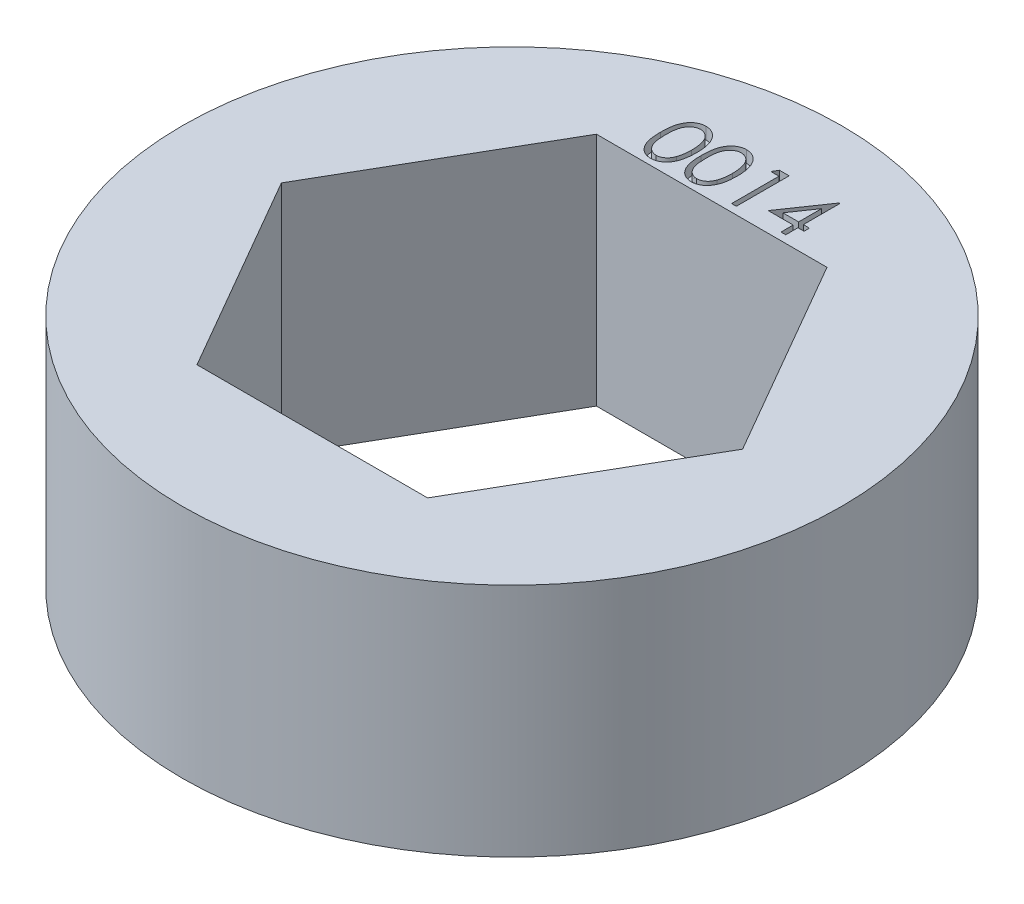
SolidWorks part; units mm, degrees
material "Nylon 101"
ref_plane "Front Plane" through (0, 0, 0) normal (0, 0, 1) x (1, 0, 0)
ref_plane "Top Plane" through (0, 0, 0) normal (0, 1, 0) x (1, 0, 0)
ref_plane "Right Plane" through (0, 0, 0) normal (1, 0, 0) x (0, 0, -1)
sketch "Sketch1" plane through (0, 0, 0) normal (0, 1, 0) x (1, 0, 0)
  line L1 (7.7723, 0) -> (3.8861, 6.731)
  line L2 (3.8861, 6.731) -> (-3.8861, 6.731)
  line L3 (-3.8861, 6.731) -> (-7.7723, 0)
  line L4 (-7.7723, 0) -> (-3.8861, -6.731)
  line L5 (-3.8861, -6.731) -> (3.8861, -6.731)
  line L6 (3.8861, -6.731) -> (7.7723, 0)
  circle A0 centre (0, 0) radius 11.1125
  circle A1 centre (0, 0) radius 6.731 construction
  dimension "D1" = 22.225
  dimension "D2" = 13.462
extrude "Boss-Extrude1" add sketch "Sketch1" along normal blind 7.9375
sketch "Sketch2" plane through (0, 7.9375, 0) normal (0, 1, 0) x (1, 0, 0)
  line L0 (-2.9329, 6.985) -> (2.7996, 6.985) construction
  line L1 (3.8861, 6.731) -> (-3.8861, 6.731) construction
  text T0 "0014" font "Century Gothic" height 1.778
  dimension "D1" = 0.254
extrude "Cut-Extrude1" cut sketch "Sketch2" against normal blind 0.4
